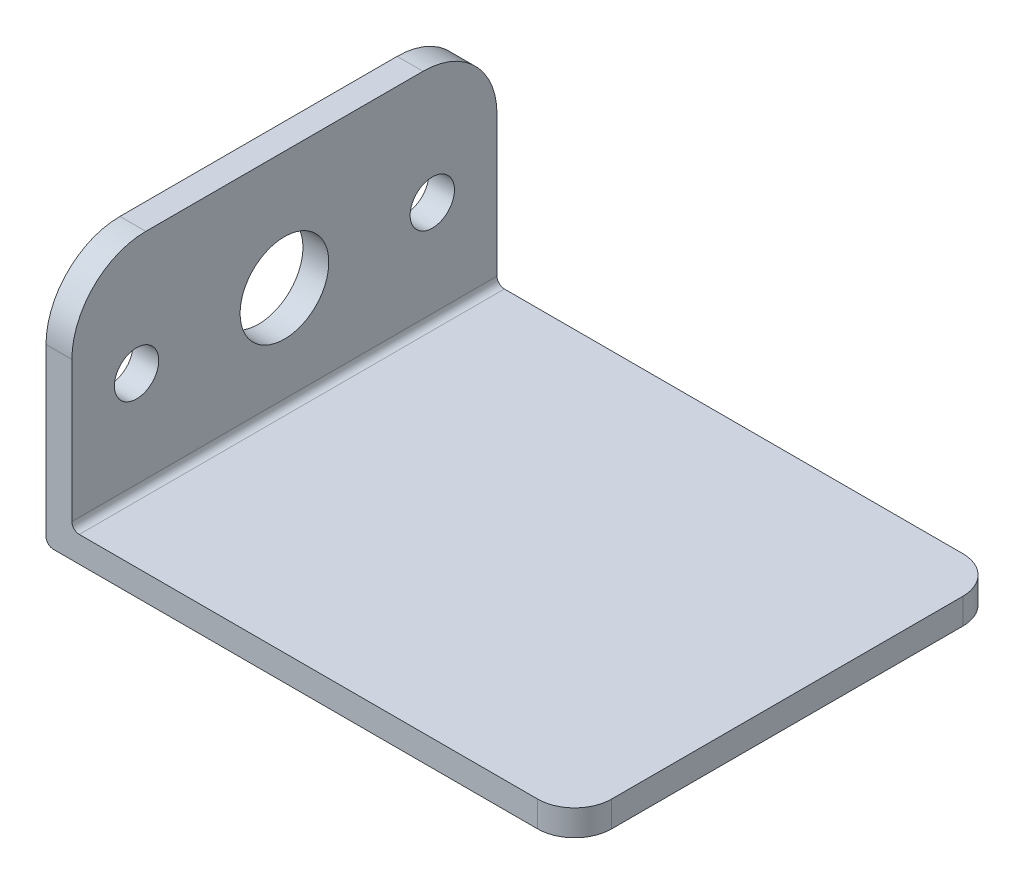
SolidWorks part; units mm, degrees
ref_plane "Alzado" through (0, 0, 0) normal (0, 0, 1) x (1, 0, 0)
ref_plane "Planta" through (0, 0, 0) normal (0, 1, 0) x (1, 0, 0)
ref_plane "Vista lateral" through (0, 0, 0) normal (1, 0, 0) x (0, 0, -1)
sketch "Croquis1" plane through (0, 0, 0) normal (0, 0, 1) x (1, 0, 0)
  line L0 (0, 33.5) -> (0, 0)
  line L1 (0, 0) -> (71.5, 0)
  line L3 (3.5, 3.5) -> (71.5, 3.5)
  line L4 (71.5, 0) -> (71.5, 3.5)
  line L7 (0, 33.5) -> (3.5, 33.5)
  line L8 (3.5, 3.5) -> (3.5, 33.5)
  dimension "D1" = 3.5
  dimension "D2" = 3.5
  dimension "D3" = 30
  dimension "D4" = 68
extrude "Saliente-Extruir1" add sketch "Croquis1" along normal mid plane 57.5
fillet "Redondeo1" radius 5 2 edges at (71.5, 1.75, -28.75) (71.5, 1.75, 28.75)
fillet "Redondeo2" radius 10 2 edges at (1.75, 33.5, -28.75) (1.75, 33.5, 28.75)
fillet "Redondeo3" radius 1 2 edges at (0, 0, 0) (3.5, 3.5, 0)
sketch "Croquis2" plane through (3.5, 0, 0) normal (1, 0, 0) x (0, 0, -1)
  line L1 (-23.75, 3.5) -> (23.75, 3.5) construction
  circle A0 centre (0, 17.5) radius 3
  circle A1 centre (20, 17.5) radius 3
  circle A2 centre (-20, 17.5) radius 3
  dimension "D1" = 6
  dimension "D2" = 14
  dimension "D3" = 20
  dimension "D4" = 20
extrude "Cortar-Extruir1" cut sketch "Croquis2" against normal up to next
sketch "Croquis3" plane through (0, 0, 0) normal (1, 0, 0) x (0, 0, -1)
  line L0 (-28.75, 0) -> (-28.75, 23.5)
  line L1 (-18.75, 33.5) -> (18.75, 33.5) construction
  line L2 (-18.75, 33.5) -> (18.75, 33.5)
  line L3 (28.75, 23.5) -> (28.75, 4.5)
  line L4 (28.75, 4.5) -> (28.75, 0)
  line L5 (28.75, 0) -> (-28.75, 0)
  arc A0 (-28.75, 23.5) -> (-18.75, 33.5) centre (-18.75, 23.5) cw
  arc A1 (-18.75, 33.5) -> (-28.75, 23.5) centre (-18.75, 23.5) ccw construction
  arc A2 (18.75, 33.5) -> (28.75, 23.5) centre (18.75, 23.5) cw
  dimension "D1" = 10
  dimension "D2" = 23.5
  dimension "D3" = 37.5
  dimension "D4" = 57.5
extrude "Cortar-Extruir2" cut sketch "Croquis4" against normal through all both and the other way through all
sketch "Croquis4" plane through (-28.4, 19.0373, -123.4359) normal (1, 0, 0) x (0, 0.866, -0.5)
  line L1 (-98.7976, 98.7976) -> (-148.4924, 148.4924) construction
  line L4 (-83.9483, 113.6468) -> (-113.6468, 83.9483) construction
  circle A4 centre (-98.7976, 98.7976) radius 9.65 construction
  circle A7 centre (-98.7976, 98.7976) radius 6
  circle A8 centre (-73.0493, 123.4505) radius 3
  circle A9 centre (-53.0493, 88.8095) radius 3
  circle A10 centre (-63.0493, 106.13) radius 6
  circle A14 centre (28.7351, 4.9664) radius 3
  circle A15 centre (22.1792, -13.3605) radius 3
  circle A22 centre (6.5, 11.2583) radius 2.4
  circle A23 centre (13, 0) radius 2.4
  circle A24 centre (6.5, -11.2583) radius 2.4
  circle A25 centre (-6.5, -11.2583) radius 2.4
  circle A26 centre (-13, 0) radius 2.4
  circle A27 centre (-6.5, 11.2583) radius 2.4
  point P3 (-105.6212, 105.6212)
  point P10 (-116.2278, 116.2278)
